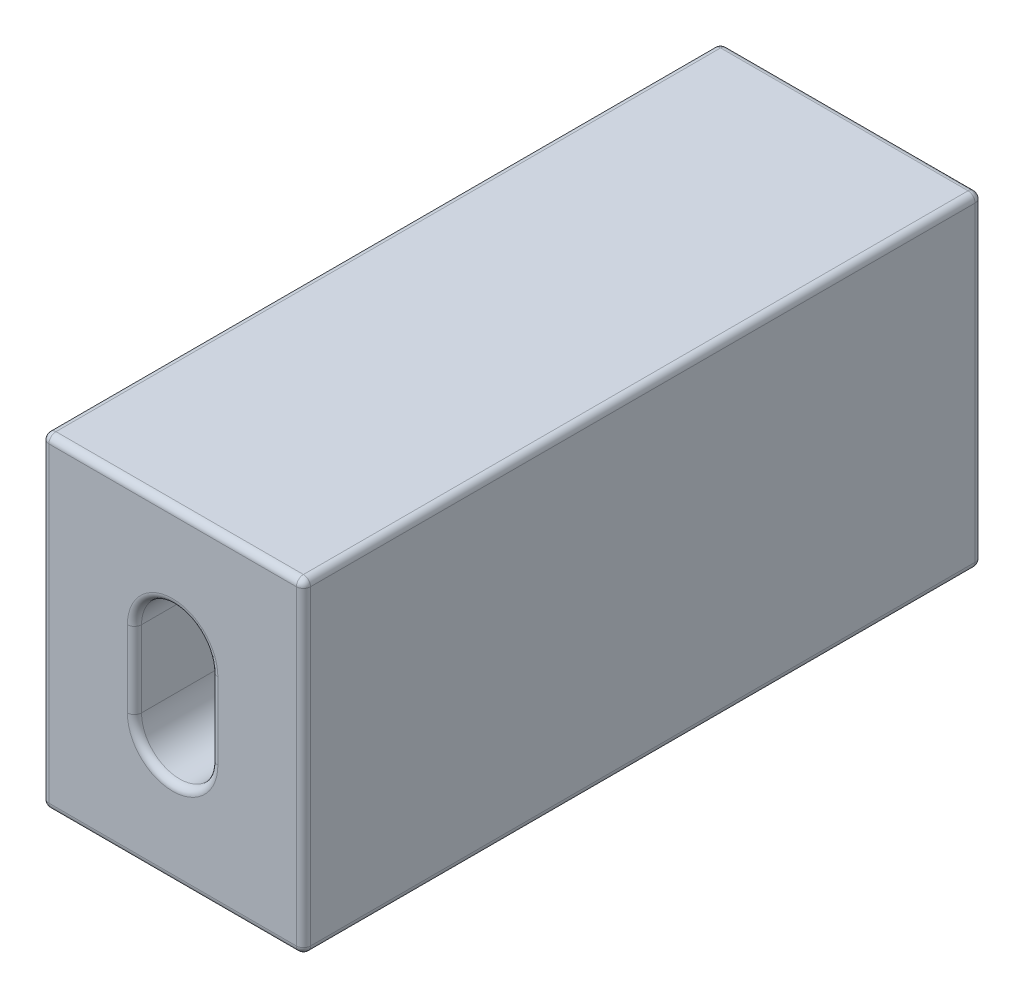
SolidWorks part; units mm, degrees
ref_plane "Спереди" through (0, 0, 0) normal (0, 0, 1) x (1, 0, 0)
ref_plane "Сверху" through (0, 0, 0) normal (0, 1, 0) x (1, 0, 0)
ref_plane "Справа" through (0, 0, 0) normal (1, 0, 0) x (0, 0, -1)
sketch "Эскиз1" plane through (0, 0, 0) normal (0, 0, 1) x (1, 0, 0)
  line L1 (0.7, 3.35) -> (18.2, 3.35)
  line L2 (0.2, 3.85) -> (0.2, 25.85)
  line L3 (0.7, 26.35) -> (18.2, 26.35)
  line L4 (18.7, 3.85) -> (18.7, 25.85)
  line L6 (6.75, 17.55) -> (6.75, 12.15)
  line L8 (12.15, 17.55) -> (12.15, 12.15)
  arc A0 (0.2, 25.85) -> (0.7, 26.35) centre (0.7, 25.85) cw
  arc A1 (18.2, 26.35) -> (18.7, 25.85) centre (18.2, 25.85) cw
  arc A6 (18.2, 3.35) -> (18.7, 3.85) centre (18.2, 3.85) ccw
  arc A7 (0.7, 3.35) -> (0.2, 3.85) centre (0.7, 3.85) cw
  arc A9 (6.75, 12.15) -> (12.15, 12.15) centre (9.45, 12.15) ccw
  arc A10 (12.15, 17.55) -> (6.75, 17.55) centre (9.45, 17.55) ccw
  dimension "D1" = 0.5
  dimension "D6" = 23
  dimension "D7" = 0.5
  dimension "D2" = 2
  dimension "D3" = 5.4
  dimension "D9" = 8.8
  dimension "D4" = 5.4
  dimension "D5" = 18.5
  dimension "D8" = 6.55
extrude "Бобышка-Вытянуть1" add sketch "Эскиз1" along normal blind 48
fillet "Скругление1" radius 0.5 12 edges at (12.15, 14.85, 0) (6.75, 14.85, 0) (0.2, 14.85, 0) (0.3464, 3.4964, 0) (9.45, 3.35, 0) (18.5536, 3.4964, 0) (18.7, 14.85, 0) (18.5536, 26.2036, 0) (9.45, 26.35, 0) (0.3464, 26.2036, 0) (9.45, 9.45, 0) (9.45, 20.25, 0)
fillet "Скругление2" radius 0.5 12 edges at (12.15, 14.85, 48) (6.75, 14.85, 48) (9.45, 26.35, 48) (18.5536, 26.2036, 48) (18.7, 14.85, 48) (18.5536, 3.4964, 48) (9.45, 3.35, 48) (0.3464, 3.4964, 48) (0.2, 14.85, 48) (0.3464, 26.2036, 48) (9.45, 9.45, 48) (9.45, 20.25, 48)
